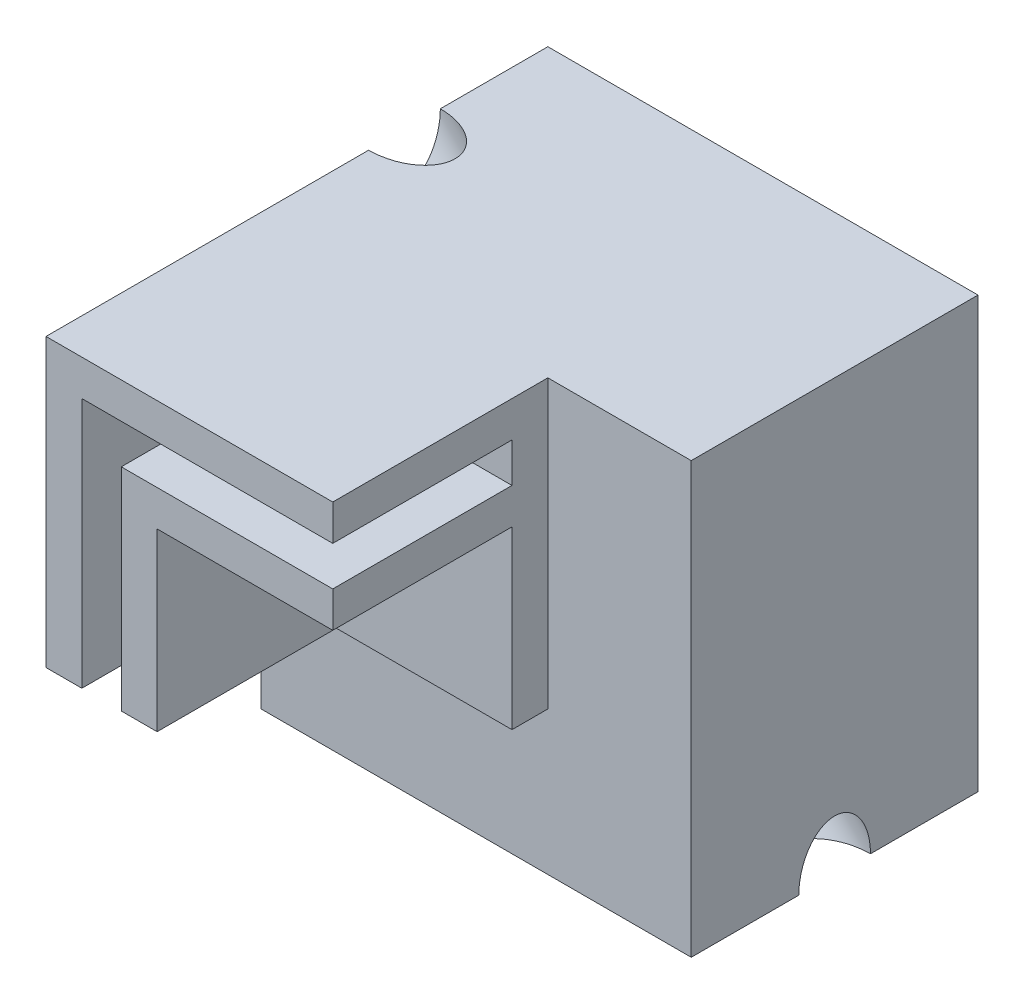
SolidWorks part; units mm, degrees
ref_plane "Alzado" through (0, 0, 0) normal (0, 0, 1) x (1, 0, 0)
ref_plane "Planta" through (0, 0, 0) normal (0, 1, 0) x (1, 0, 0)
ref_plane "Vista lateral" through (0, 0, 0) normal (1, 0, 0) x (0, 0, -1)
sketch "Croquis1" plane through (0, 0, 0) normal (0, 0, 1) x (1, 0, 0)
  line L0 (-5, 5) -> (35, 5)
  line L1 (0, 0) -> (5.5, 0)
  line L2 (0, 0) -> (0, -30)
  line L3 (0, -30) -> (5.5, -30)
  line L4 (5.5, -5.5) -> (5.5, -30)
  line L5 (0, 0) -> (30, 0)
  line L6 (0, 0) -> (0, -5.5)
  line L7 (5.5, -5.5) -> (30, -5.5)
  line L8 (30, 0) -> (30, -5.5)
  line L9 (35, 5) -> (35, -10.5)
  line L10 (10.5, -10.5) -> (35, -10.5)
  line L11 (10.5, -10.5) -> (10.5, -35)
  line L12 (-5, -35) -> (10.5, -35)
  line L13 (-5, 5) -> (-5, -35)
  line L14 (0, -30) -> (0, -35)
  line L15 (0, -35) -> (5.5, -35)
  line L16 (5.5, -35) -> (5.5, -30)
  dimension "D1" = 5.5
  dimension "D2" = 5.5
  dimension "D3" = 30
  dimension "D4" = 30
  dimension "D5" = 5
extrude "Saliente-Extruir1" add sketch "Croquis1" along normal blind 30 contours L0 L9 L10 L11 L12 L13
sketch "Croquis3" plane through (0, 0, 30) normal (0, 0, 1) x (1, 0, 0)
  line L6 (0, -30) -> (0, -35)
  line L7 (-5, -35) -> (10.5, -35) construction
  line L8 (0, -35) -> (5.5, -35)
  line L9 (5.5, -35) -> (5.5, -30)
  line L10 (30, 0) -> (35, 0)
  line L11 (35, 5) -> (35, -10.5) construction
  line L12 (0, 0) -> (0, -30)
  line L13 (0, -30) -> (5.5, -30)
  line L14 (5.5, -30) -> (5.5, -5.5)
  line L15 (5.5, -5.5) -> (30, -5.5)
  line L16 (30, -5.5) -> (30, 0)
  line L17 (30, 0) -> (0, 0)
  line L18 (0, 0) -> (0, -30)
  line L20 (5.5, -30) -> (5.5, -5.5)
  line L21 (5.5, -5.5) -> (30, -5.5)
  line L23 (30, 0) -> (0, 0)
  line L24 (35, 0) -> (35, -5.5)
  line L25 (35, -5.5) -> (30, -5.5)
  dimension "D1" = 5
extrude "Cortar-Extruir1" cut sketch "Croquis3" against normal blind 25
sketch "Croquis4" plane through (0, 0, 0) normal (0, 0, -1) x (-1, 0, 0)
  line L1 (-35, -10.5) -> (-10.5, -10.5)
  line L2 (-35, -10.5) -> (-35, -35)
  line L3 (-35, -35) -> (-10.5, -35)
  line L4 (-10.5, -10.5) -> (-10.5, -35)
extrude "Saliente-Extruir2" add sketch "Croquis4" against normal up to surface (5 mm away) up to face at (13.5, -13.5, 5)
sketch "Croquis5" plane through (0, 0, 0) normal (0, 0, -1) x (-1, 0, 0)
  line L1 (5, 5) -> (-35, 5)
  line L2 (5, 5) -> (5, -35)
  line L3 (5, -35) -> (-35, -35)
  line L4 (-35, 5) -> (-35, -35)
  line L5 (-35, 5) -> (-55, 5)
  line L6 (-35, 5) -> (-35, -35)
  line L7 (-35, -35) -> (-55, -35)
  line L8 (-55, 5) -> (-55, -35)
  line L9 (5, -35) -> (-55, -35)
  line L10 (5, -35) -> (5, -55)
  line L11 (5, -55) -> (-55, -55)
  line L12 (-55, -35) -> (-55, -55)
  dimension "D1" = 60
  dimension "D2" = 60
extrude "Saliente-Extruir4" add sketch "Croquis5" along normal blind 40 contours L6 L5 L8 L7 | L2 L1 L4 L3 | L10 L9 L12 L11
ref_plane "Plano1" through (25, -25, 0) normal (0.7071, -0.7071, 0) x (0, 0, 1)
sketch "Croquis9" plane through (25, -25, 0) normal (0.7071, -0.7071, 0) x (0, 0, 1)
  line L0 (-40, 0) -> (0, 0) construction
  circle A0 centre (-20, 0) radius 5
  dimension "D1" = 10
extrude "Cortar-Extruir5" cut sketch "Croquis9" against normal through all both and the other way through all
